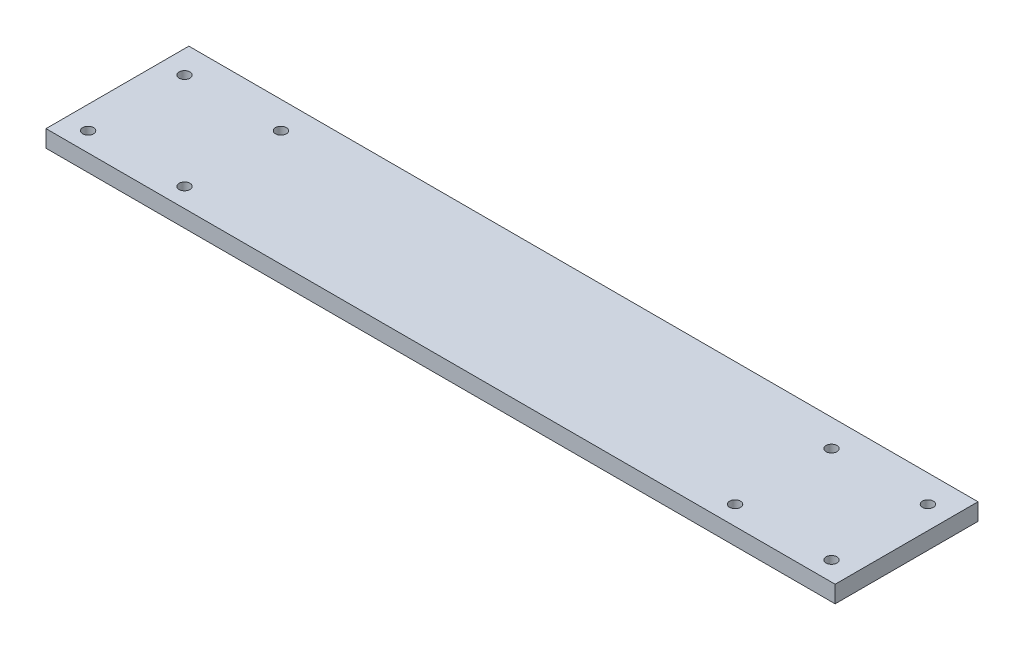
SolidWorks part; units mm, degrees
material "AISI 1020 Steel, Cold Rolled"
ref_plane "Front Plane" through (0, 0, 0) normal (0, 0, 1) x (1, 0, 0)
ref_plane "Top Plane" through (0, 0, 0) normal (0, 1, 0) x (1, 0, 0)
ref_plane "Right Plane" through (0, 0, 0) normal (1, 0, 0) x (0, 0, -1)
sketch "Sketch1" plane through (0, 0, 0) normal (0, 1, 0) x (1, 0, 0)
  line L0 (0, 28.6178) -> (0, -20.5269) construction
  line L1 (73.66, 0) -> (-73.66, 0)
  line L2 (73.66, 0) -> (73.66, 26.67)
  line L3 (73.66, 26.67) -> (-73.66, 26.67)
  line L4 (-73.66, 0) -> (-73.66, 26.67)
  line L5 (-69.3885, 21.59) -> (-51.3885, 21.59) construction
  line L6 (-60.3885, 21.59) -> (-60.3885, 0) construction
  line L7 (51.3885, 21.59) -> (69.3885, 21.59) construction
  line L8 (60.3885, 21.59) -> (60.3885, 0) construction
  circle A0 centre (51.3885, 21.59) radius 1.016
  circle A1 centre (69.3885, 21.59) radius 1.016
  circle A2 centre (51.3885, 3.59) radius 1.016
  circle A3 centre (69.3885, 3.59) radius 1.016
  circle A4 centre (-69.3885, 3.59) radius 1.016
  circle A5 centre (-51.3885, 3.59) radius 1.016
  circle A6 centre (-69.3885, 21.59) radius 1.016
  circle A7 centre (-51.3885, 21.59) radius 1.016
  point P0 (0, 0)
  dimension "D5" = 60.3885
  dimension "D6" = 18
  dimension "D7" = 2.032
  dimension "D1" = 26.67
  dimension "D2" = 73.66
  dimension "D3" = 5.08
  dimension "D4" = 18
extrude "Boss-Extrude1" add sketch "Sketch1" along normal blind 3.175
